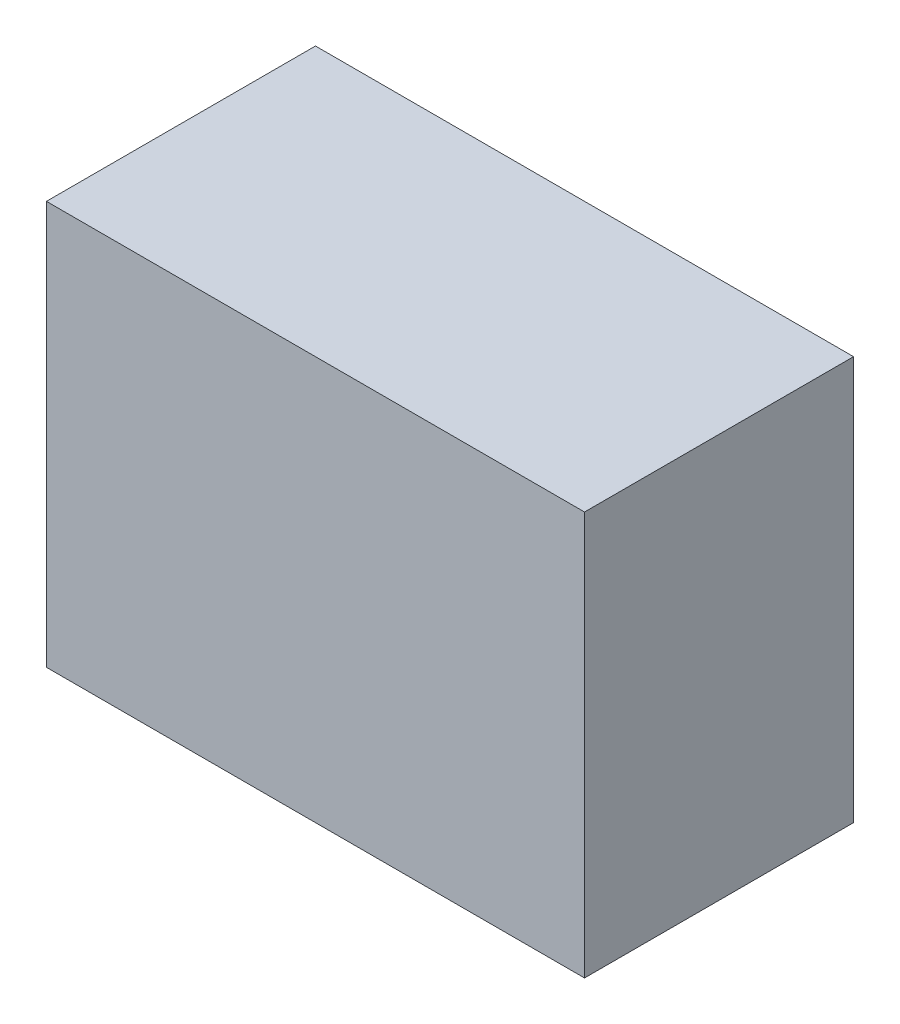
SolidWorks part; units mm, degrees
ref_plane "Front Plane" through (0, 0, 0) normal (0, 0, 1) x (1, 0, 0)
ref_plane "Top Plane" through (0, 0, 0) normal (0, 1, 0) x (1, 0, 0)
ref_plane "Right Plane" through (0, 0, 0) normal (1, 0, 0) x (0, 0, -1)
sketch "Sketch1" plane through (0, 0, 0) normal (0, 0, 1) x (1, 0, 0)
  line L1 (-10, -7.5) -> (10, -7.5)
  line L2 (-10, -7.5) -> (-10, 7.5)
  line L3 (-10, 7.5) -> (10, 7.5)
  line L4 (10, -7.5) -> (10, 7.5)
  line L5 (-10, -7.5) -> (10, 7.5) construction
  line L6 (-10, 7.5) -> (10, -7.5) construction
  point P0 (0, 0)
extrude "Boss-Extrude1" add sketch "Sketch1" against normal blind 10
ref_plane "Plane_10" through (0, 0, 0) normal (0, 0, 1) x (1, 0, 0)
sketch "Sketch2" plane through (0, 0, 0) normal (0, 0, 1) x (1, 0, 0)
  line L1 (-6.5, -4.5) -> (6.5, -4.5)
  line L2 (-6.5, -4.5) -> (-6.5, 4.5)
  line L3 (-6.5, 4.5) -> (6.5, 4.5)
  line L4 (6.5, -4.5) -> (6.5, 4.5)
  line L5 (-6.5, -4.5) -> (6.5, 4.5) construction
  line L6 (-6.5, 4.5) -> (6.5, -4.5) construction
  point P0 (0, 0)
extrude "Boss-Extrude2" add sketch "Sketch2" against normal blind 5
